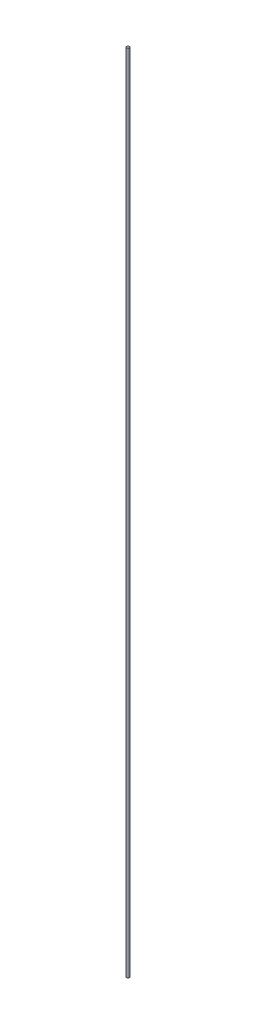
SolidWorks part; units mm, degrees
ref_plane "Front Plane" through (0, 0, 0) normal (0, 0, 1) x (1, 0, 0)
ref_plane "Top Plane" through (0, 0, 0) normal (0, 1, 0) x (1, 0, 0)
ref_plane "Right Plane" through (0, 0, 0) normal (1, 0, 0) x (0, 0, -1)
sketch "Sketch1" plane through (0, 0, 0) normal (0, 1, 0) x (1, 0, 0)
  circle A0 centre (0, 0) radius 2.5
  dimension "D1" = 5
extrude "Boss-Extrude1" add sketch "Sketch1" along normal blind 1500
